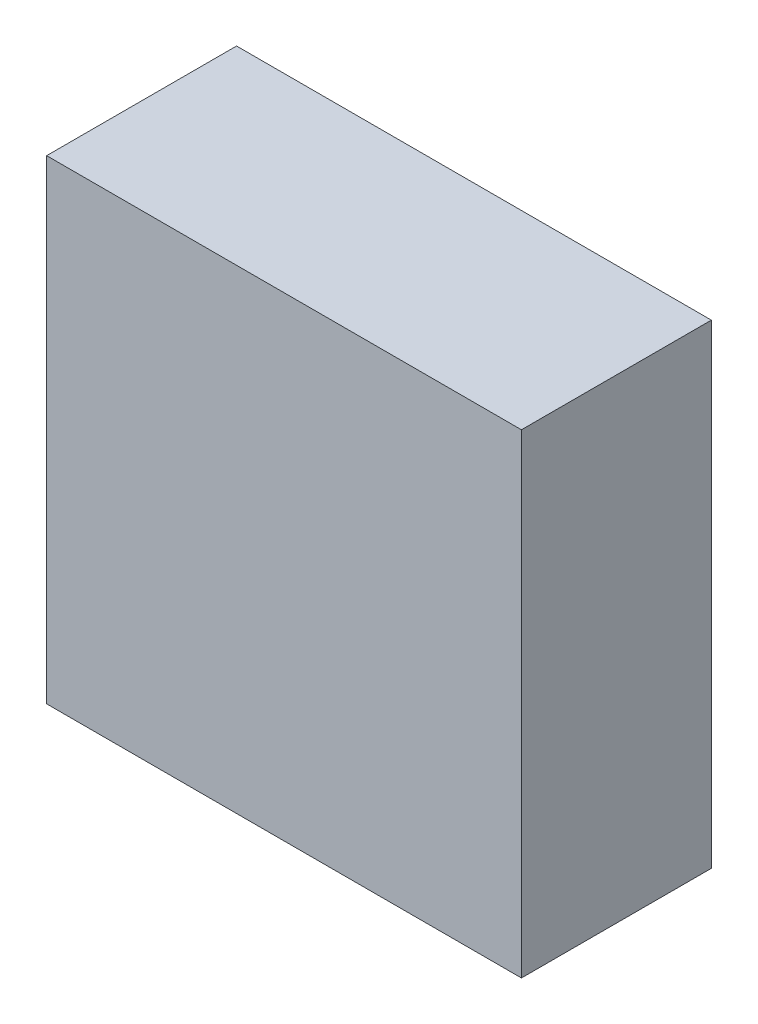
SolidWorks part; units mm, degrees
ref_plane "前视基准面" through (0, 0, 0) normal (0, 0, 1) x (1, 0, 0)
ref_plane "上视基准面" through (0, 0, 0) normal (0, 1, 0) x (1, 0, 0)
ref_plane "右视基准面" through (0, 0, 0) normal (1, 0, 0) x (0, 0, -1)
other "Configuration Table"
sketch "草图1" plane through (0, 0, 0) normal (0, 0, 1) x (1, 0, 0)
  line L1 (-25, -25) -> (25, -25)
  line L2 (-25, -25) -> (-25, 25)
  line L3 (-25, 25) -> (25, 25)
  line L4 (25, -25) -> (25, 25)
  line L5 (-25, -25) -> (25, 25) construction
  line L6 (-25, 25) -> (25, -25) construction
  point P0 (0, 0)
extrude "凸台-拉伸1" add sketch "草图1" along normal blind 20
